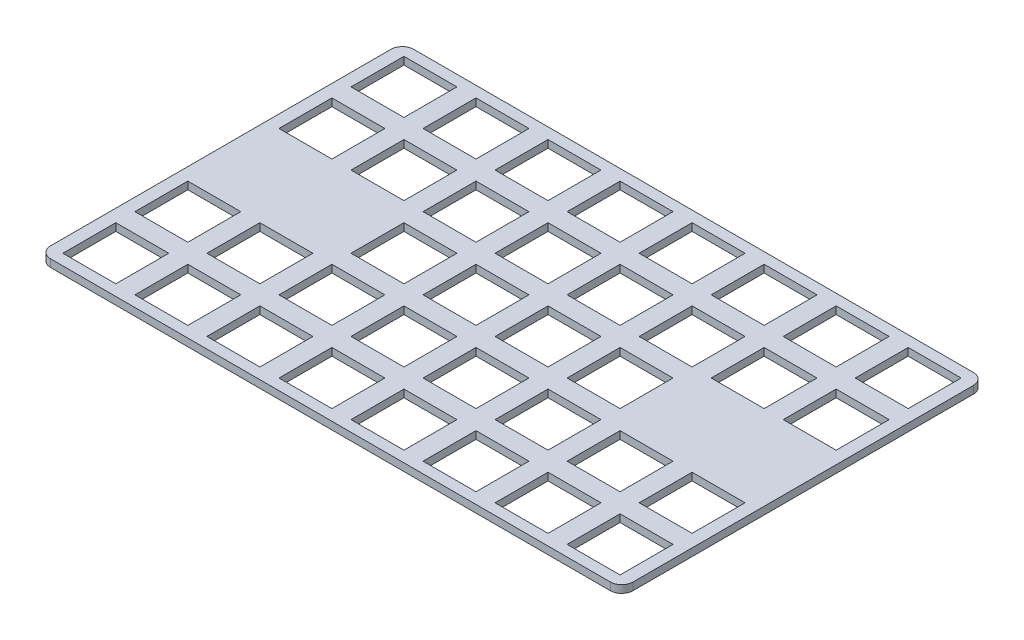
SolidWorks part; units mm, degrees
ref_plane "Front Plane" through (0, 0, 0) normal (0, 0, 1) x (1, 0, 0)
ref_plane "Top Plane" through (0, 0, 0) normal (0, 1, 0) x (1, 0, 0)
ref_plane "Right Plane" through (0, 0, 0) normal (1, 0, 0) x (0, 0, -1)
sketch "Sketch14" plane through (0, 0, 0) normal (0, 1, 0) x (1, 0, 0)
  line L0 (0, 90.2) -> (147.35, 0) construction
  line L8 (19.05, 0) -> (19.05, 14)
  line L9 (0, 0) -> (14, 0)
  line L10 (0, 0) -> (0, 14)
  line L11 (0, 14) -> (14, 14)
  line L12 (14, 0) -> (14, 14)
  line L13 (19.05, 0) -> (33.05, 0)
  line L14 (33.05, 0) -> (33.05, 14)
  line L15 (19.05, 14) -> (33.05, 14)
  line L16 (38.1, 0) -> (38.1, 14)
  line L17 (38.1, 0) -> (52.1, 0)
  line L18 (52.1, 0) -> (52.1, 14)
  line L19 (38.1, 14) -> (52.1, 14)
  line L20 (57.15, 0) -> (57.15, 14)
  line L21 (57.15, 0) -> (71.15, 0)
  line L22 (71.15, 0) -> (71.15, 14)
  line L23 (57.15, 14) -> (71.15, 14)
  line L24 (76.2, 0) -> (76.2, 14)
  line L25 (76.2, 0) -> (90.2, 0)
  line L26 (90.2, 0) -> (90.2, 14)
  line L27 (76.2, 14) -> (90.2, 14)
  line L28 (95.25, 0) -> (95.25, 14)
  line L29 (95.25, 0) -> (109.25, 0)
  line L30 (109.25, 0) -> (109.25, 14)
  line L31 (95.25, 14) -> (109.25, 14)
  line L32 (114.3, 0) -> (114.3, 14)
  line L33 (114.3, 0) -> (128.3, 0)
  line L34 (128.3, 0) -> (128.3, 14)
  line L35 (114.3, 14) -> (128.3, 14)
  line L36 (133.35, 0) -> (133.35, 14)
  line L37 (133.35, 0) -> (147.35, 0)
  line L38 (147.35, 0) -> (147.35, 14)
  line L39 (133.35, 14) -> (147.35, 14)
  line L40 (19.05, 19.05) -> (19.05, 33.05)
  line L41 (19.05, 19.05) -> (33.05, 19.05)
  line L42 (33.05, 19.05) -> (33.05, 33.05)
  line L43 (19.05, 33.05) -> (33.05, 33.05)
  line L44 (38.1, 19.05) -> (38.1, 33.05)
  line L45 (38.1, 19.05) -> (52.1, 19.05)
  line L46 (52.1, 19.05) -> (52.1, 33.05)
  line L47 (38.1, 33.05) -> (52.1, 33.05)
  line L48 (57.15, 19.05) -> (57.15, 33.05)
  line L49 (57.15, 19.05) -> (71.15, 19.05)
  line L50 (71.15, 19.05) -> (71.15, 33.05)
  line L51 (57.15, 33.05) -> (71.15, 33.05)
  line L52 (76.2, 19.05) -> (76.2, 33.05)
  line L53 (76.2, 19.05) -> (90.2, 19.05)
  line L54 (90.2, 19.05) -> (90.2, 33.05)
  line L55 (76.2, 33.05) -> (90.2, 33.05)
  line L56 (95.25, 19.05) -> (95.25, 33.05)
  line L57 (95.25, 19.05) -> (109.25, 19.05)
  line L58 (109.25, 19.05) -> (109.25, 33.05)
  line L59 (95.25, 33.05) -> (109.25, 33.05)
  line L60 (114.3, 19.05) -> (114.3, 33.05)
  line L61 (114.3, 19.05) -> (128.3, 19.05)
  line L62 (128.3, 19.05) -> (128.3, 33.05)
  line L63 (114.3, 33.05) -> (128.3, 33.05)
  line L64 (133.35, 19.05) -> (133.35, 33.05)
  line L65 (133.35, 19.05) -> (147.35, 19.05)
  line L66 (147.35, 19.05) -> (147.35, 33.05)
  line L67 (133.35, 33.05) -> (147.35, 33.05)
  line L68 (19.05, 38.1) -> (19.05, 52.1) [skipped]
  line L69 (19.05, 38.1) -> (33.05, 38.1) [skipped]
  line L70 (33.05, 38.1) -> (33.05, 52.1) [skipped]
  line L71 (19.05, 52.1) -> (33.05, 52.1) [skipped]
  line L72 (38.1, 38.1) -> (38.1, 52.1)
  line L73 (38.1, 38.1) -> (52.1, 38.1)
  line L74 (52.1, 38.1) -> (52.1, 52.1)
  line L75 (38.1, 52.1) -> (52.1, 52.1)
  line L76 (57.15, 38.1) -> (57.15, 52.1)
  line L77 (57.15, 38.1) -> (71.15, 38.1)
  line L78 (71.15, 38.1) -> (71.15, 52.1)
  line L79 (57.15, 52.1) -> (71.15, 52.1)
  line L80 (76.2, 38.1) -> (76.2, 52.1)
  line L81 (76.2, 38.1) -> (90.2, 38.1)
  line L82 (90.2, 38.1) -> (90.2, 52.1)
  line L83 (76.2, 52.1) -> (90.2, 52.1)
  line L84 (95.25, 38.1) -> (95.25, 52.1)
  line L85 (95.25, 38.1) -> (109.25, 38.1)
  line L86 (109.25, 38.1) -> (109.25, 52.1)
  line L87 (95.25, 52.1) -> (109.25, 52.1)
  line L88 (114.3, 38.1) -> (114.3, 52.1) [skipped]
  line L89 (114.3, 38.1) -> (128.3, 38.1) [skipped]
  line L90 (128.3, 38.1) -> (128.3, 52.1) [skipped]
  line L91 (114.3, 52.1) -> (128.3, 52.1) [skipped]
  line L92 (133.35, 38.1) -> (133.35, 52.1) [skipped]
  line L93 (133.35, 38.1) -> (147.35, 38.1) [skipped]
  line L94 (147.35, 38.1) -> (147.35, 52.1) [skipped]
  line L95 (133.35, 52.1) -> (147.35, 52.1) [skipped]
  line L96 (19.05, 57.15) -> (19.05, 71.15)
  line L97 (19.05, 57.15) -> (33.05, 57.15)
  line L98 (33.05, 57.15) -> (33.05, 71.15)
  line L99 (19.05, 71.15) -> (33.05, 71.15)
  line L100 (38.1, 57.15) -> (38.1, 71.15)
  line L101 (38.1, 57.15) -> (52.1, 57.15)
  line L102 (52.1, 57.15) -> (52.1, 71.15)
  line L103 (38.1, 71.15) -> (52.1, 71.15)
  line L104 (57.15, 57.15) -> (57.15, 71.15)
  line L105 (57.15, 57.15) -> (71.15, 57.15)
  line L106 (71.15, 57.15) -> (71.15, 71.15)
  line L107 (57.15, 71.15) -> (71.15, 71.15)
  line L108 (76.2, 57.15) -> (76.2, 71.15)
  line L109 (76.2, 57.15) -> (90.2, 57.15)
  line L110 (90.2, 57.15) -> (90.2, 71.15)
  line L111 (76.2, 71.15) -> (90.2, 71.15)
  line L112 (95.25, 57.15) -> (95.25, 71.15)
  line L113 (95.25, 57.15) -> (109.25, 57.15)
  line L114 (109.25, 57.15) -> (109.25, 71.15)
  line L115 (95.25, 71.15) -> (109.25, 71.15)
  line L116 (114.3, 57.15) -> (114.3, 71.15)
  line L117 (114.3, 57.15) -> (128.3, 57.15)
  line L118 (128.3, 57.15) -> (128.3, 71.15)
  line L119 (114.3, 71.15) -> (128.3, 71.15)
  line L120 (133.35, 57.15) -> (133.35, 71.15)
  line L121 (133.35, 57.15) -> (147.35, 57.15)
  line L122 (147.35, 57.15) -> (147.35, 71.15)
  line L123 (133.35, 71.15) -> (147.35, 71.15)
  line L124 (19.05, 76.2) -> (19.05, 90.2)
  line L125 (19.05, 76.2) -> (33.05, 76.2)
  line L126 (33.05, 76.2) -> (33.05, 90.2)
  line L127 (19.05, 90.2) -> (33.05, 90.2)
  line L128 (38.1, 76.2) -> (38.1, 90.2)
  line L129 (38.1, 76.2) -> (52.1, 76.2)
  line L130 (52.1, 76.2) -> (52.1, 90.2)
  line L131 (38.1, 90.2) -> (52.1, 90.2)
  line L132 (57.15, 76.2) -> (57.15, 90.2)
  line L133 (57.15, 76.2) -> (71.15, 76.2)
  line L134 (71.15, 76.2) -> (71.15, 90.2)
  line L135 (57.15, 90.2) -> (71.15, 90.2)
  line L136 (76.2, 76.2) -> (76.2, 90.2)
  line L137 (76.2, 76.2) -> (90.2, 76.2)
  line L138 (90.2, 76.2) -> (90.2, 90.2)
  line L139 (76.2, 90.2) -> (90.2, 90.2)
  line L140 (95.25, 76.2) -> (95.25, 90.2)
  line L141 (95.25, 76.2) -> (109.25, 76.2)
  line L142 (109.25, 76.2) -> (109.25, 90.2)
  line L143 (95.25, 90.2) -> (109.25, 90.2)
  line L144 (114.3, 76.2) -> (114.3, 90.2)
  line L145 (114.3, 76.2) -> (128.3, 76.2)
  line L146 (128.3, 76.2) -> (128.3, 90.2)
  line L147 (114.3, 90.2) -> (128.3, 90.2)
  line L148 (133.35, 76.2) -> (133.35, 90.2)
  line L149 (133.35, 76.2) -> (147.35, 76.2)
  line L150 (147.35, 76.2) -> (147.35, 90.2)
  line L151 (133.35, 90.2) -> (147.35, 90.2)
  line L152 (0, 19.05) -> (0, 33.05)
  line L153 (0, 19.05) -> (14, 19.05)
  line L154 (14, 19.05) -> (14, 33.05)
  line L155 (0, 33.05) -> (14, 33.05)
  line L156 (0, 38.1) -> (0, 52.1) [skipped]
  line L157 (0, 38.1) -> (14, 38.1) [skipped]
  line L158 (14, 38.1) -> (14, 52.1) [skipped]
  line L159 (0, 52.1) -> (14, 52.1) [skipped]
  line L160 (0, 57.15) -> (0, 71.15)
  line L161 (0, 57.15) -> (14, 57.15)
  line L162 (14, 57.15) -> (14, 71.15)
  line L163 (0, 71.15) -> (14, 71.15)
  line L164 (0, 76.2) -> (0, 90.2)
  line L165 (0, 76.2) -> (14, 76.2)
  line L166 (14, 76.2) -> (14, 90.2)
  line L167 (0, 90.2) -> (14, 90.2)
  point P4 (73.675, 45.1)
  point P5 (0, 0)
  dimension "D1" = 14
  dimension "D2" = 14
  dimension "D3" = 8
  dimension "D4" = 5
  dimension "D5" = 19.05
  dimension "D6" = 19.05
sketch "Sketch16" plane through (0, 0, 0) normal (0, 1, 0) x (1, 0, 0)
  line L1 (-0.325, 93.1) -> (147.675, 93.1)
  line L2 (-3.325, 90.1) -> (-3.325, 0.1)
  line L3 (-0.325, -2.9) -> (147.675, -2.9)
  line L4 (150.675, 90.1) -> (150.675, 0.1)
  line L8 (-2.4463, 92.2213) -> (149.7963, -2.0213) construction
  arc A0 (-3.325, 0.1) -> (-0.325, -2.9) centre (-0.325, 0.1) ccw
  arc A1 (147.675, -2.9) -> (150.675, 0.1) centre (147.675, 0.1) ccw
  arc A2 (147.675, 93.1) -> (150.675, 90.1) centre (147.675, 90.1) cw
  arc A3 (-0.325, 93.1) -> (-3.325, 90.1) centre (-0.325, 90.1) ccw
  dimension "D5" = 3
  dimension "D1" = 154
  dimension "D2" = 96
extrude "Boss-Extrude1" add sketch "Sketch16" along normal blind 2
extrude "Cut-Extrude3" cut sketch "Sketch14" against normal through all and the other way through all
